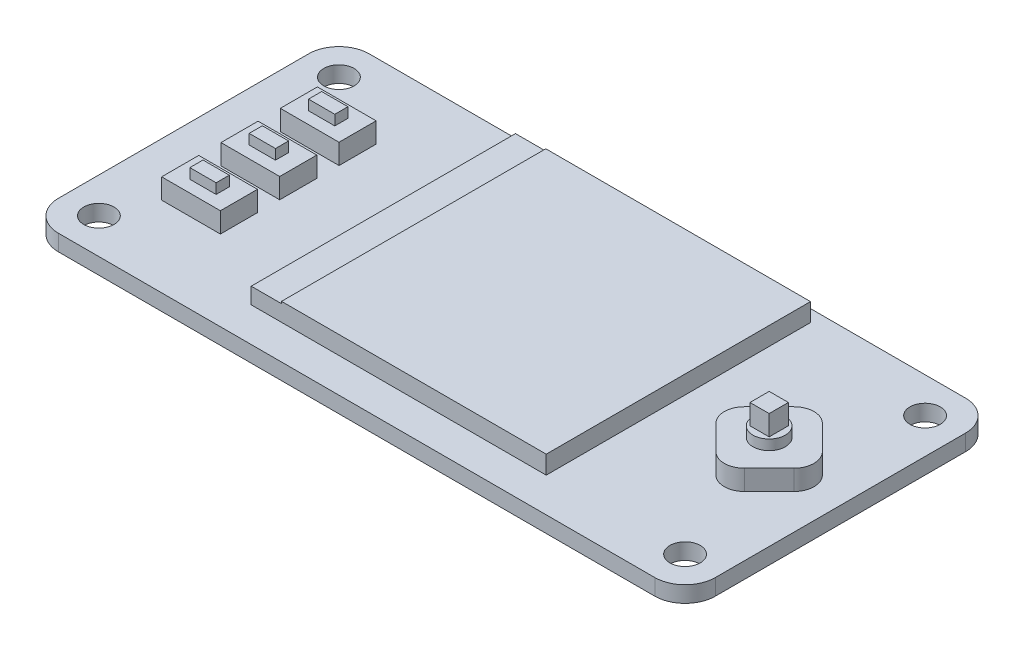
SolidWorks part; units mm, degrees
ref_plane "前视基准面" through (0, 0, 0) normal (0, 0, 1) x (1, 0, 0)
ref_plane "上视基准面" through (0, 0, 0) normal (0, 1, 0) x (1, 0, 0)
ref_plane "右视基准面" through (0, 0, 0) normal (1, 0, 0) x (0, 0, -1)
sketch "草图1" plane through (0, 0, 0) normal (0, 1, 0) x (1, 0, 0)
  line L1 (-29.5, 15.375) -> (29.5, 15.375)
  line L2 (-32.5, 12.375) -> (-32.5, -12.375)
  line L3 (-29.5, -15.375) -> (29.5, -15.375)
  line L4 (32.5, 12.375) -> (32.5, -12.375)
  line L5 (-32.5, 15.375) -> (32.5, -15.375) construction
  line L6 (-32.5, -15.375) -> (32.5, 15.375) construction
  arc A0 (-32.5, -12.375) -> (-29.5, -15.375) centre (-29.5, -12.375) ccw
  arc A1 (29.5, -15.375) -> (32.5, -12.375) centre (29.5, -12.375) ccw
  arc A2 (29.5, 15.375) -> (32.5, 12.375) centre (29.5, 12.375) cw
  arc A3 (-29.5, 15.375) -> (-32.5, 12.375) centre (-29.5, 12.375) ccw
  point P0 (0, 0)
  dimension "D3" = 3
  dimension "D1" = 30.75
  dimension "D2" = 65
extrude "凸台-拉伸1" add sketch "草图1" along normal blind 1.6
sketch "草图2" plane through (0, 1.6, 0) normal (0, 1, 0) x (1, 0, 0)
  line L0 (29.5, 15.375) -> (-29.5, 15.375) construction
  line L2 (-32.5, 12.375) -> (-32.5, -12.375) construction
  line L3 (-29.5, -15.375) -> (29.5, -15.375) construction
  line L4 (32.5, -12.375) -> (32.5, 12.375) construction
  circle A0 centre (-29, 11.875) radius 1.5
  circle A1 centre (-29, -11.875) radius 1.5
  circle A2 centre (29, -11.875) radius 1.5
  circle A3 centre (29, 11.875) radius 1.5
  point P12 (0, 0)
  point P14 (-37.6889, -6.1013)
  dimension "D1" = 3
  dimension "D2" = 3.5
  dimension "D3" = 3.5
  dimension "D4" = 3.5
  dimension "D5" = 3.5
extrude "切除-拉伸1" cut sketch "草图2" against normal blind 1.6
sketch "草图3" plane through (0, 1.6, 0) normal (0, 1, 0) x (1, 0, 0)
  line L0 (-29.5, -15.375) -> (29.5, -15.375) construction
  line L1 (-13.83, 14.175) -> (15.36, 14.175)
  line L2 (-13.83, 14.175) -> (-13.83, -11.975)
  line L3 (-13.83, -11.975) -> (15.36, -11.975)
  line L4 (15.36, 14.175) -> (15.36, -11.975)
  line L7 (32.5, -12.375) -> (32.5, 12.375) construction
  dimension "D1" = 26.15
  dimension "D2" = 29.19
  dimension "D3" = 3.4
  dimension "D4" = 17.14
sketch "草图4" plane through (0, 1.6, 0) normal (0, 1, 0) x (1, 0, 0)
  line L0 (-29.5, -15.375) -> (29.5, -15.375) construction
  line L1 (-27.23, 7.975) -> (-21.42, 7.975)
  line L2 (-27.23, 7.975) -> (-27.23, 4.305)
  line L3 (-27.23, 4.305) -> (-21.42, 4.305)
  line L4 (-21.42, 7.975) -> (-21.42, 4.305)
  line L5 (-27.23, 2.105) -> (-21.42, 2.105)
  line L6 (-27.23, 2.105) -> (-27.23, -1.565)
  line L7 (-27.23, -1.565) -> (-21.42, -1.565)
  line L8 (-21.42, 2.105) -> (-21.42, -1.565)
  line L9 (-27.23, -3.765) -> (-21.42, -3.765)
  line L10 (-27.23, -3.765) -> (-27.23, -7.435)
  line L11 (-27.23, -7.435) -> (-21.42, -7.435)
  line L12 (-21.42, -3.765) -> (-21.42, -7.435)
  line L13 (-32.5, 12.375) -> (-32.5, -12.375) construction
  dimension "D1" = 5.81
  dimension "D2" = 3.67
  dimension "D3" = 2.2
  dimension "D4" = 2.2
  dimension "D5" = 7.94
  dimension "D6" = 5.27
sketch "草图5" plane through (0, 1.6, 0) normal (0, 1, 0) x (1, 0, 0)
  line L0 (26.5747, 4.1383) -> (29.0142, 1.6987)
  line L1 (23.7463, 4.1383) -> (21.3067, 1.6987)
  line L2 (29.0142, -1.1297) -> (26.5747, -3.5692)
  line L3 (21.3067, -1.1297) -> (23.7463, -3.5692)
  line L4 (32.5, -12.375) -> (32.5, 12.375) construction
  line L5 (-29.5, -15.375) -> (29.5, -15.375) construction
  arc A0 (26.5747, -3.5692) -> (23.7463, -3.5692) centre (25.1605, -2.155) cw
  arc A1 (21.3067, 1.6987) -> (21.3067, -1.1297) centre (22.721, 0.2845) ccw
  arc A2 (23.7463, 4.1383) -> (26.5747, 4.1383) centre (25.1605, 2.724) cw
  arc A3 (29.0142, 1.6987) -> (29.0142, -1.1297) centre (27.6, 0.2845) cw
  point P8 (19.8925, 0.2845)
  point P11 (25.1605, 5.5525)
  point P14 (30.4284, 0.2845)
  point P15 (29.6, 0.2845)
  point P18 (25.1605, -4.155)
  dimension "D3" = 2
  dimension "D1" = 7.45
  dimension "D2" = 7.45
  dimension "D4" = 2.9
  dimension "D5" = 11.22
extrude "凸台-拉伸2" add sketch "草图3" along normal blind 1.8
extrude "凸台-拉伸3" add sketch "草图5" along normal blind 2
sketch "草图6" plane through (0, 3.4, 0) normal (0, 1, 0) x (1, 0, 0)
  line L0 (-13.83, -11.975) -> (15.36, -11.975) construction
  line L1 (-13.83, 14.175) -> (-10.83, 14.175)
  line L2 (-13.83, 14.175) -> (-13.83, -11.975)
  line L3 (-13.83, -11.975) -> (-10.83, -11.975)
  line L4 (-10.83, 14.175) -> (-10.83, -11.975)
  dimension "D1" = 3
extrude "切除-拉伸2" cut sketch "草图6" against normal blind 0.2
extrude "凸台-拉伸4" add sketch "草图4" along normal blind 2
sketch "草图7" plane through (0, 3.6, 0) normal (0, 1, 0) x (1, 0, 0)
  line L0 (-21.42, 7.975) -> (-27.23, 7.975) construction
  line L1 (-25.625, 6.79) -> (-23.025, 6.79)
  line L2 (-25.625, 6.79) -> (-25.625, 5.49)
  line L3 (-25.625, 5.49) -> (-23.025, 5.49)
  line L4 (-23.025, 6.79) -> (-23.025, 5.49)
  line L5 (-25.625, 6.79) -> (-23.025, 5.49) construction
  line L6 (-25.625, 5.49) -> (-23.025, 6.79) construction
  line L7 (-25.625, 0.92) -> (-23.025, 0.92)
  line L8 (-25.625, 0.92) -> (-25.625, -0.38)
  line L9 (-25.625, -0.38) -> (-23.025, -0.38)
  line L10 (-23.025, 0.92) -> (-23.025, -0.38)
  line L11 (-25.625, 0.92) -> (-23.025, -0.38) construction
  line L12 (-25.625, -0.38) -> (-23.025, 0.92) construction
  line L13 (-25.625, -4.95) -> (-23.025, -4.95)
  line L14 (-25.625, -4.95) -> (-25.625, -6.25)
  line L15 (-25.625, -6.25) -> (-23.025, -6.25)
  line L16 (-23.025, -4.95) -> (-23.025, -6.25)
  line L17 (-25.625, -4.95) -> (-23.025, -6.25) construction
  line L18 (-25.625, -6.25) -> (-23.025, -4.95) construction
  line L19 (-27.23, -3.765) -> (-27.23, -7.435) construction
  line L20 (-27.23, 2.105) -> (-27.23, -1.565) construction
  line L21 (-27.23, 7.975) -> (-27.23, 4.305) construction
  point P0 (-24.325, 6.14)
  point P5 (-24.325, 0.27)
  point P10 (-24.325, -5.6)
  point P18 (-24.325, 7.975)
  point P22 (-27.23, -5.6)
  point P26 (-27.23, 0.27)
  point P30 (-27.23, 6.14)
  dimension "D1" = 2.6
  dimension "D2" = 1.3
extrude "凸台-拉伸5" add sketch "草图7" along normal blind 1
sketch "草图8" plane through (0, 0, 0) normal (0, -1, 0) x (1, 0, 0)
  line L0 (29.5, -15.375) -> (-29.5, -15.375) construction
  line L1 (-25.7, -8.735) -> (25.3, -8.735)
  line L2 (-25.7, -8.735) -> (-25.7, -13.735)
  line L3 (-25.7, -13.735) -> (25.3, -13.735)
  line L4 (25.3, -8.735) -> (25.3, -13.735)
  line L5 (32.5, 12.375) -> (32.5, -12.375) construction
  dimension "D1" = 5
  dimension "D2" = 51
  dimension "D3" = 1.64
  dimension "D4" = 7.2
extrude "凸台-拉伸6" add sketch "草图8" along normal blind 3.68
sketch "草图9" plane through (0, 3.6, 0) normal (0, 1, 0) x (1, 0, 0)
  line L1 (24.2105, 1.2345) -> (26.1105, 1.2345)
  line L2 (24.2105, 1.2345) -> (24.2105, -0.6655)
  line L3 (24.2105, -0.6655) -> (26.1105, -0.6655)
  line L4 (26.1105, 1.2345) -> (26.1105, -0.6655)
  line L5 (24.2105, 1.2345) -> (26.1105, -0.6655) construction
  line L6 (24.2105, -0.6655) -> (26.1105, 1.2345) construction
  arc A0 (29.0142, -1.1297) -> (29.0142, 1.6987) centre (27.6, 0.2845) ccw construction
  arc A1 (26.5747, 4.1383) -> (23.7463, 4.1383) centre (25.1605, 2.724) ccw construction
  point P0 (25.1605, 0.2845)
  point P11 (29.6, 0.2845)
  point P16 (25.1605, 4.724)
  dimension "D1" = 1.9
extrude "凸台-拉伸7" add sketch "草图9" along normal blind 3
sketch "草图10" plane through (0, 3.6, 0) normal (0, 1, 0) x (1, 0, 0)
  line L0 (26.1105, 1.2345) -> (24.2105, 1.2345) construction
  line L2 (26.1105, -0.6655) -> (26.1105, 1.2345) construction
  circle A0 centre (25.1605, 0.2845) radius 1.6
  point P2 (0, 0)
  point P5 (25.1605, 1.2345)
  point P8 (0, 0)
  point P11 (26.1105, 0.2845)
  dimension "D1" = 3.2
extrude "凸台-拉伸8" add sketch "草图10" along normal blind 1
